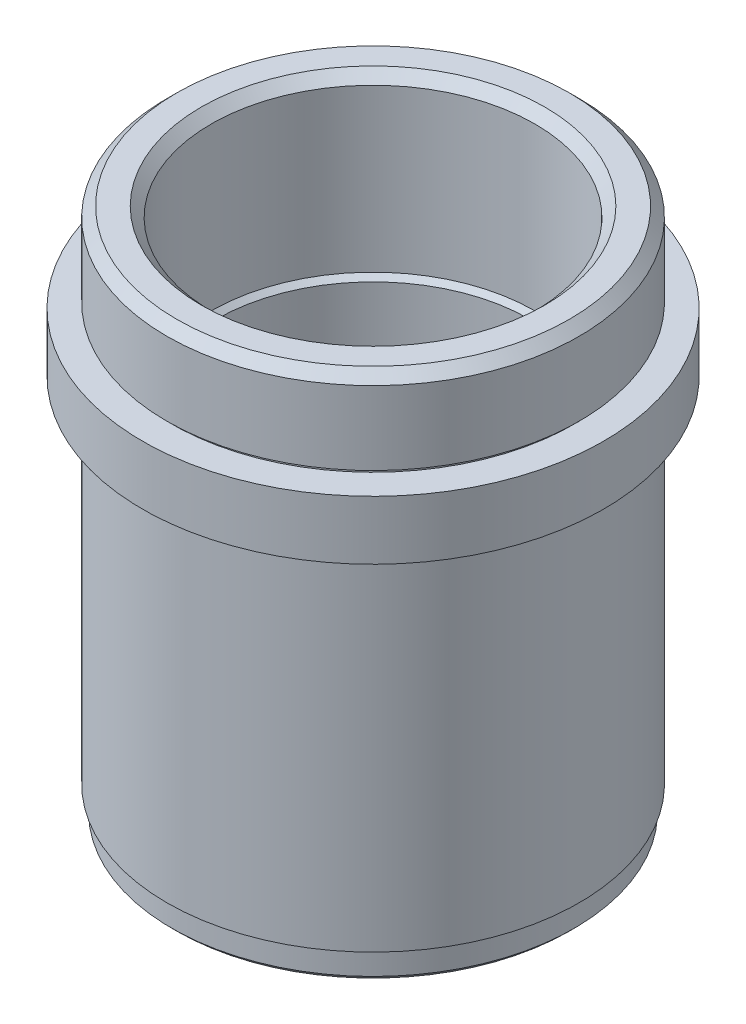
SolidWorks part; units mm, degrees
ref_plane "Płaszczyzna przednia" through (0, 0, 0) normal (0, 0, 1) x (1, 0, 0)
ref_plane "Płaszczyzna górna" through (0, 0, 0) normal (0, 1, 0) x (1, 0, 0)
ref_plane "Płaszczyzna prawa" through (0, 0, 0) normal (1, 0, 0) x (0, 0, -1)
sketch "Szkic1" plane through (0, 0, 0) normal (0, 0, 1) x (1, 0, 0)
  line L0 (0, 0) -> (0, 59.9954) construction
  line L1 (-17.5, 59.9954) -> (-20, 59.9954)
  line L2 (-21, 58.9954) -> (-21, 51.5)
  line L3 (-20.5, 50.9954) -> (-23.5, 50.9954)
  line L4 (-23.5, 50.9954) -> (-23.5, 44.9954)
  line L5 (-23.5, 44.9954) -> (-20.5, 44.9954)
  line L6 (-21, 44.5) -> (-21, 8.9954)
  line L7 (-20, 5.9954) -> (-16, 5.9954)
  line L8 (-21, 8.9954) -> (-20.5, 8.9954)
  line L9 (-20, 59.9954) -> (-21, 58.9954)
  line L10 (-16.5, 58.9954) -> (-16.5, 42.4954)
  line L11 (-21, 51.5) -> (-20.5, 51.5)
  line L12 (-20.5, 51.5) -> (-20.5, 50.9954)
  line L13 (-20.5, 44.9954) -> (-20.5, 44.5)
  line L14 (-20.5, 44.5) -> (-21, 44.5)
  line L15 (-16.5, 58.9954) -> (-17.5, 59.9954)
  line L16 (-20.5, 8.9954) -> (-20.5, 6.4954)
  line L17 (-20.5, 6.4954) -> (-20, 5.9954)
  line L18 (-16, 5.9954) -> (-16, 41.9954)
  line L19 (-16, 41.9954) -> (-16.5, 42.4954)
  point P4 (-21, 59.9954)
  point P8 (-16.5, 59.9954)
  point P22 (-20.5, 5.9954)
  dimension "D1" = 6
  dimension "D2" = 9
  dimension "D3" = 3
  dimension "D4" = 23.5
  dimension "D5" = 21
  dimension "D7" = 21
  dimension "D8" = 16.5
  dimension "D9" = 20.5
  dimension "D10" = 45
  dimension "D12" = 16
  dimension "D13" = 36
revolve "Obrót1" add sketch "Szkic1" angle 360 about L0
